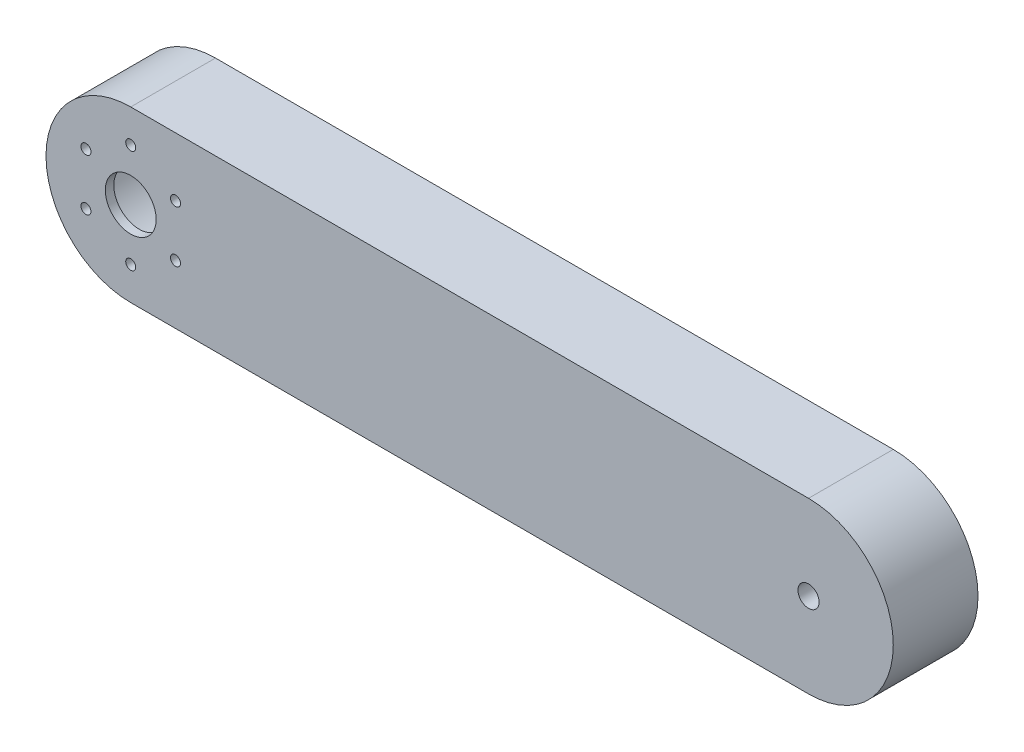
SolidWorks part; units mm, degrees
ref_plane "Front Plane" through (0, 0, 0) normal (0, 0, 1) x (1, 0, 0)
ref_plane "Top Plane" through (0, 0, 0) normal (0, 1, 0) x (1, 0, 0)
ref_plane "Right Plane" through (0, 0, 0) normal (1, 0, 0) x (0, 0, -1)
sketch "Sketch1" plane through (0, 0, 0) normal (0, 0, 1) x (1, 0, 0)
  line L1 (-101.6, -25.4) -> (101.6, -25.4)
  line L2 (-101.6, -25.4) -> (-101.6, 25.4)
  line L3 (-101.6, 25.4) -> (101.6, 25.4)
  line L4 (101.6, -25.4) -> (101.6, 25.4)
  line L5 (-101.6, -25.4) -> (101.6, 25.4) construction
  line L6 (-101.6, 25.4) -> (101.6, -25.4) construction
  circle A0 centre (-101.6, 0) radius 25.4
  circle A1 centre (101.6, 0) radius 25.4
  circle A2 centre (-101.6, 0) radius 19.05
  point P0 (0, 0)
  dimension "D3" = 38.1
  dimension "D1" = 50.8
  dimension "D2" = 203.2
extrude "Boss-Extrude1" add sketch "Sketch1" along normal blind 25.4 contours A0 | L2 L1 L4 L3 | A1
sketch "Sketch2" plane through (0, 0, 0) normal (0, 0, 1) x (1, 0, 0)
  circle A0 centre (-101.6, 0) radius 19.05
  arc A1 (-101.6, 25.4) -> (-101.6, -25.4) centre (-101.6, 0) ccw construction
  circle A2 centre (101.6, 0) radius 19.05
  arc A3 (101.6, -25.4) -> (101.6, 25.4) centre (101.6, 0) ccw construction
  dimension "D1" = 38.1
  dimension "D2" = 38.1
extrude "Cut-Extrude1" cut sketch "Sketch2" along normal offset from surface (22.86 mm away) 2.54 contours A0 up to face at (0, 0, 25.4)
sketch "Sketch3" plane through (0, 0, 25.4) normal (0, 0, 1) x (1, 0, 0)
  circle A0 centre (101.6, 0) radius 3.175
  arc A1 (101.6, -25.4) -> (101.6, 25.4) centre (101.6, 0) ccw construction
  dimension "D1" = 6.35
sketch "Sketch4" plane through (0, 0, 22.86) normal (0, 0, -1) x (-1, 0, 0)
  circle A0 centre (101.6, 0) radius 7.62
  circle A1 centre (101.6, 0) radius 19.05 construction
  circle A2 centre (101.6, 0) radius 15.5 construction
  circle A3 centre (101.6, 15.5) radius 1.5
  circle A4 centre (115.0234, 7.75) radius 1.5
  circle A5 centre (115.0234, -7.75) radius 1.5
  circle A6 centre (101.6, -15.5) radius 1.5
  circle A7 centre (88.1766, -7.75) radius 1.5
  circle A8 centre (88.1766, 7.75) radius 1.5
  dimension "D1" = 15.24
  dimension "D2" = 31
  dimension "D3" = 3
  dimension "D4" = 6
extrude "Cut-Extrude2" cut sketch "Sketch4" against normal through all
extrude "Cut-Extrude3" cut sketch "Sketch3" against normal through all contours A0
